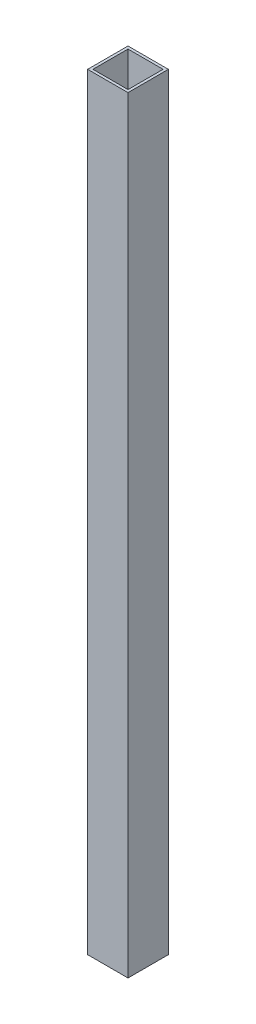
SolidWorks part; units mm, degrees
material "6061 Alloy"
ref_plane "Front Plane" through (0, 0, 0) normal (0, 0, 1) x (1, 0, 0)
ref_plane "Top Plane" through (0, 0, 0) normal (0, 1, 0) x (1, 0, 0)
ref_plane "Right Plane" through (0, 0, 0) normal (1, 0, 0) x (0, 0, -1)
sketch "Sketch1" plane through (0, 0, 0) normal (0, 1, 0) x (1, 0, 0)
  line L1 (-12.7, -12.7) -> (12.7, -12.7)
  line L2 (-12.7, -12.7) -> (-12.7, 12.7)
  line L3 (-12.7, 12.7) -> (12.7, 12.7)
  line L4 (12.7, -12.7) -> (12.7, 12.7)
  line L5 (-12.7, -12.7) -> (12.7, 12.7) construction
  line L6 (-12.7, 12.7) -> (12.7, -12.7) construction
  point P0 (0, 0)
  dimension "D1" = 25.4
  dimension "D2" = 25.4
extrude "Boss-Extrude1" add sketch "Sketch1" along normal mid plane 482.6 contours L2 L1 L4 L3
sketch "Sketch2" plane through (0, 241.3, 0) normal (0, 1, 0) x (1, 0, 0)
  line L0 (-12.7, -12.7) -> (-12.7, 12.7) construction
  line L1 (-11.049, -11.049) -> (11.049, -11.049)
  line L2 (-11.049, -11.049) -> (-11.049, 11.049)
  line L3 (-11.049, 11.049) -> (11.049, 11.049)
  line L4 (11.049, -11.049) -> (11.049, 11.049)
  line L5 (-11.049, -11.049) -> (11.049, 11.049) construction
  line L6 (-11.049, 11.049) -> (11.049, -11.049) construction
  line L7 (-12.7, 12.7) -> (12.7, 12.7) construction
  point P0 (0, 0)
  dimension "D1" = 1.651
  dimension "D2" = 1.651
extrude "Cut-Extrude1" cut sketch "Sketch2" against normal through all contours L2 L1 L4 L3
